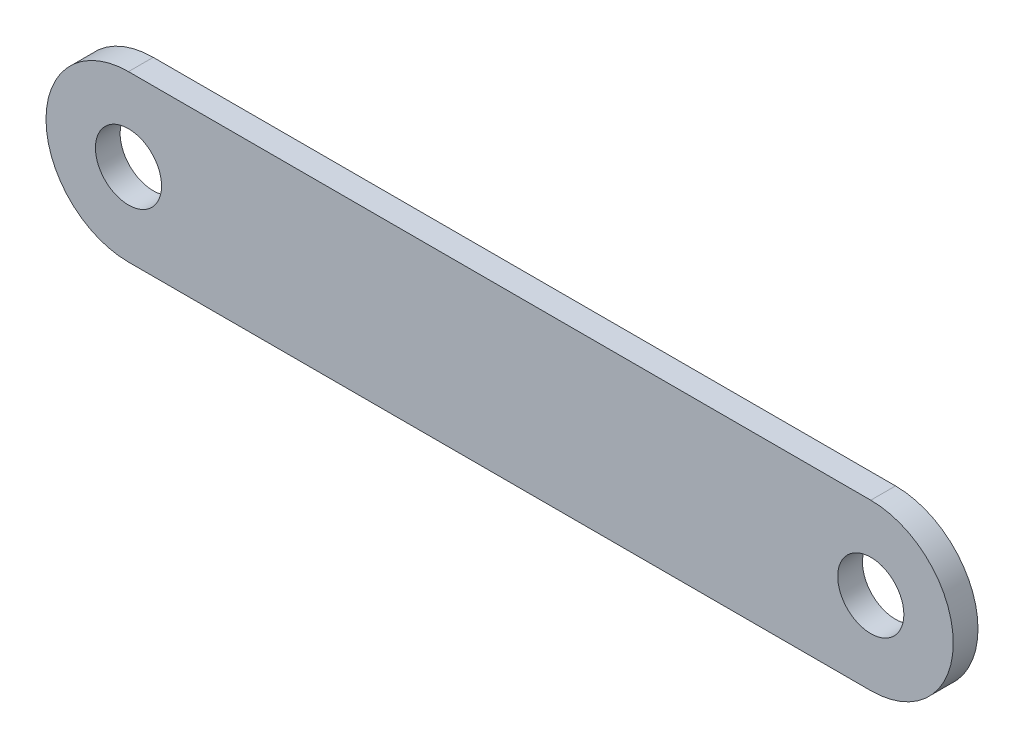
SolidWorks part; units mm, degrees
ref_plane "Front Plane" through (0, 0, 0) normal (0, 0, 1) x (1, 0, 0)
ref_plane "Top Plane" through (0, 0, 0) normal (0, 1, 0) x (1, 0, 0)
ref_plane "Right Plane" through (0, 0, 0) normal (1, 0, 0) x (0, 0, -1)
sketch "Sketch1" plane through (0, 0, 0) normal (0, 0, 1) x (1, 0, 0)
  line L0 (0, 10) -> (90, 10)
  line L1 (0, -10) -> (100, -10)
  circle A0 centre (0, 0) radius 10
  circle A1 centre (90, 0) radius 10
  dimension "D1" = 20
  dimension "D2" = 20
  dimension "D3" = 90
extrude "Boss-Extrude1" add sketch "Sketch1" along normal blind 3
sketch "Sketch2" plane through (0, 0, 3) normal (0, 0, 1) x (1, 0, 0)
  circle A0 centre (0, 0) radius 4.01
  circle A1 centre (90, 0) radius 4.01
  dimension "D1" = 8.02
  dimension "D2" = 8.02
extrude "Cut-Extrude1" cut sketch "Sketch2" against normal blind 10
